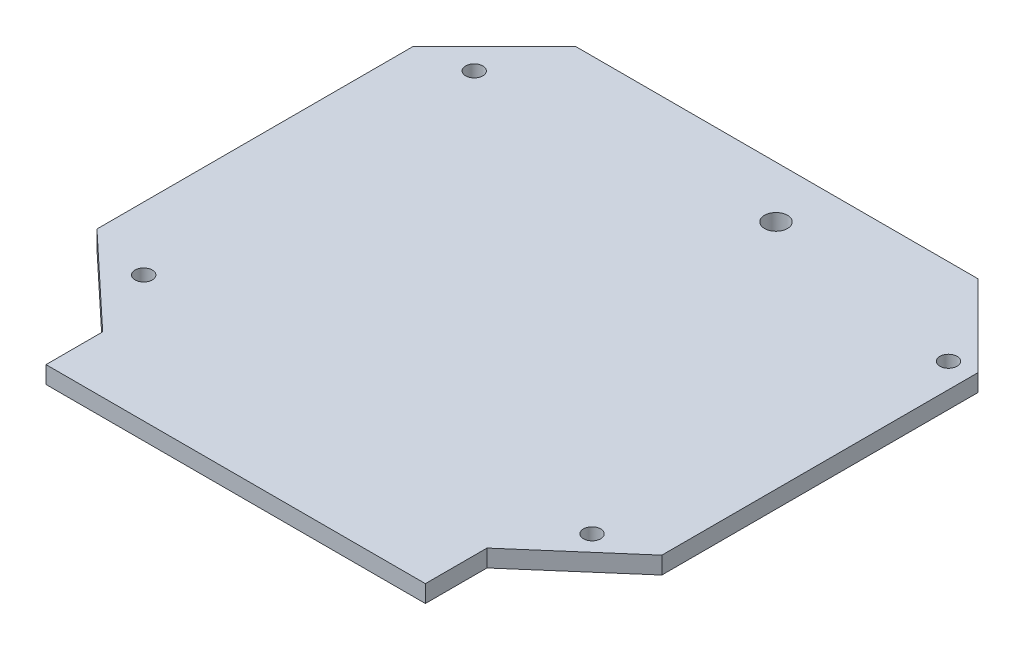
SolidWorks part; units mm, degrees
material "A-玻璃纤维"
ref_plane "前视基准面" through (0, 0, 0) normal (0, 0, 1) x (1, 0, 0)
ref_plane "上视基准面" through (0, 0, 0) normal (0, 1, 0) x (1, 0, 0)
ref_plane "右视基准面" through (0, 0, 0) normal (1, 0, 0) x (0, 0, -1)
other "Configuration Table"
sketch "草图1" plane through (0, 0, 0) normal (0, 1, 0) x (1, 0, 0)
  line L0 (0, 0) -> (121.2282, 0) construction
  line L1 (0, 0) -> (0, -76.686) construction
  line L2 (14.14, 0) -> (84.14, 0)
  line L3 (84.14, 0) -> (98.28, -14.14)
  line L4 (98.28, -14.14) -> (98.28, -69.14)
  line L5 (98.28, -69.14) -> (82, -83.28)
  line L6 (82, -83.28) -> (82, -94)
  line L7 (82, -94) -> (16, -94)
  line L8 (16, -94) -> (16, -84.14)
  line L9 (16, -84.14) -> (0, -69.14)
  line L10 (0, -69.14) -> (0, -14.14)
  line L11 (0, -14.14) -> (14.14, 0)
  circle A0 centre (9, -12.5) radius 1.5
  circle A1 centre (94, -15) radius 1.5
  circle A2 centre (11, -72) radius 1.5
  circle A3 centre (89, -72) radius 1.5
  circle A4 centre (58, -9) radius 2
  dimension "D13" = 3
  dimension "D14" = 3
  dimension "D15" = 3
  dimension "D16" = 3
  dimension "D26" = 4
  dimension "D1" = 70
  dimension "D2" = 14.14
  dimension "D3" = 14.14
  dimension "D4" = 14.14
  dimension "D5" = 55
  dimension "D6" = 14.14
  dimension "D7" = 16.28
  dimension "D8" = 66
  dimension "D9" = 94
  dimension "D10" = 84.14
  dimension "D11" = 55
  dimension "D12" = 14.14
  dimension "D17" = 12.5
  dimension "D18" = 9
  dimension "D19" = 94
  dimension "D20" = 15
  dimension "D21" = 72
  dimension "D22" = 11
  dimension "D23" = 89
  dimension "D24" = 72
  dimension "D25" = 58
  dimension "D27" = 9
extrude "凸台-拉伸1" add sketch "草图1" along normal blind 3
